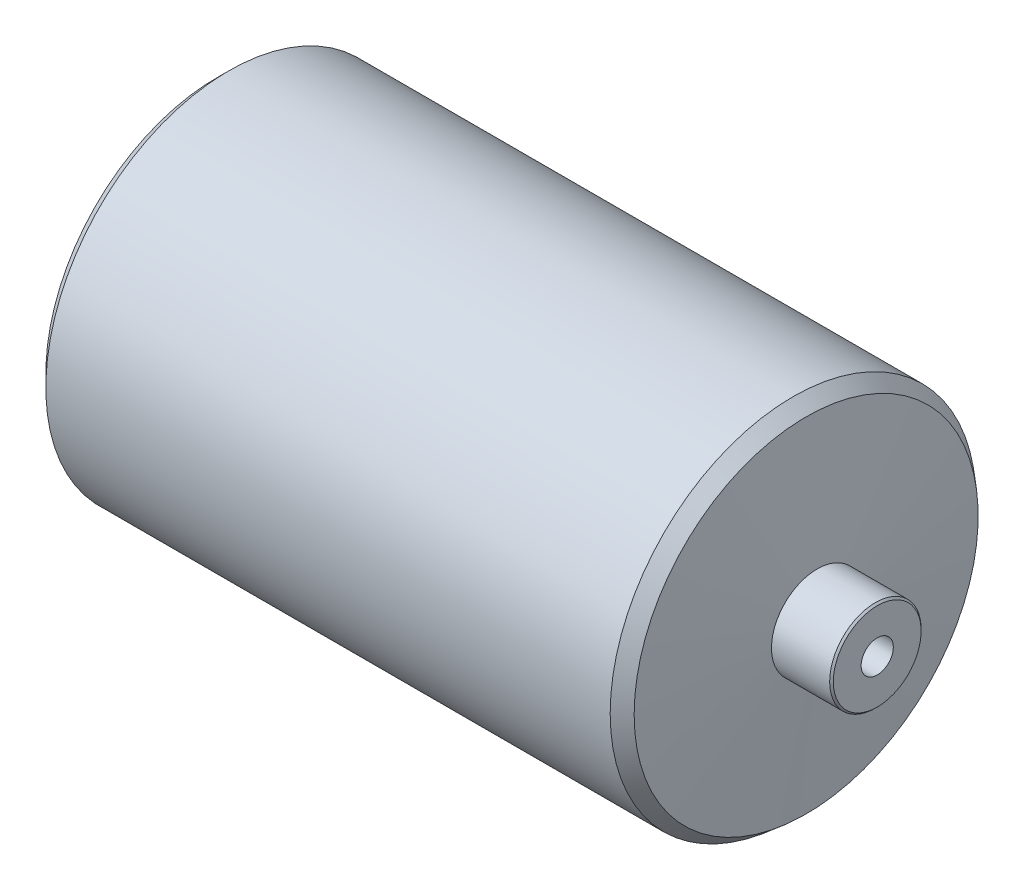
SolidWorks part; units mm, degrees
ref_plane "前基準面" through (0, 0, 0) normal (0, 0, 1) x (1, 0, 0)
ref_plane "上基準面" through (0, 0, 0) normal (0, 1, 0) x (1, 0, 0)
ref_plane "右基準面" through (0, 0, 0) normal (1, 0, 0) x (0, 0, -1)
sketch "草圖1" plane through (0, 0, 0) normal (0, 0, 1) x (1, 0, 0)
  line L1 (0, 0) -> (16.5, 0)
  line L2 (0, 0) -> (0, 12.5)
  line L3 (0, 12.5) -> (16.5, 12.5)
  line L4 (16.5, 0) -> (16.5, 12.5)
  line L5 (16.5, 0) -> (183.6, 0)
  line L6 (16.5, 0) -> (16.5, 50)
  line L7 (16.5, 50) -> (183.6, 50)
  line L8 (183.6, 0) -> (183.6, 50)
  line L9 (183.6, 0) -> (200, 0)
  line L10 (183.6, 0) -> (183.6, 12.5)
  line L11 (183.6, 12.5) -> (200, 12.5)
  line L12 (200, 0) -> (200, 12.5)
  dimension "D1" = 200
  dimension "D2" = 16.4
  dimension "D3" = 16.5
  dimension "D4" = 12.5
  dimension "D5" = 12.5
  dimension "D6" = 50
revolve "旋轉1" add sketch "草圖1" angle 360 about L5
sketch "草圖2" plane through (0, 0, 0) normal (0, 0, 1) x (1, 0, 0)
  line L0 (0, 12.5) -> (16.5, 12.5)
  line L1 (16.5, 12.5) -> (20.558, 58.8837)
  line L2 (200, 12.5) -> (183.6, 12.5)
  line L3 (183.6, -50) -> (183.6, 50) construction
  line L4 (183.6, -12.5) -> (183.6, 12.5) construction
  line L5 (183.6, 12.5) -> (178.9819, 65.2855)
  line L6 (20.558, 58.8837) -> (178.9819, 65.2855)
  line L7 (200, 12.5) -> (186.8731, 74.8434)
  line L8 (186.8731, 74.8434) -> (1.0252, 63.1739)
  line L9 (1.0252, 63.1739) -> (0, 12.5)
  line L10 (0, 0) -> (-38.6891, 0)
  dimension "D1" = 95
  dimension "D2" = 95
revolve "除料-旋轉1" cut sketch "草圖2" angle 360 about L10
chamfer "導角1" distance 0.5 angle 45 2 edges at (200, 0, 12.5) (0, 0, 12.5)
chamfer "導角2" distance 3 angle 45 2 edges at (180.3192, 0, 50) (19.7808, 0, -50)
hole_wizard "M10x1.25 螺紋孔1" positions "3D草圖1" profile "草圖5" tap size "M10x1.25" standard "ISO"
sketch3d "3D草圖1"
  circle A0 centre (200, 0, 0) radius 12 construction
  circle A1 centre (200, 0, 0) radius 12
  point P0 (200, 0, 0)
  point P3 (0, 0, 0)
  point P6 (212, 0, 0)
  point P8 (212, 0, 0)
  point P9 (200, 0, 0)
sketch "草圖5" plane through (200, 0, 0) normal (0, 1, 0) x (0, 0, -1)
  line L0 (0, 0) -> (0, 61.6438)
  line L1 (0, 61.6438) -> (4.4, 59)
  line L2 (4.4, 59) -> (4.4, 0)
  line L5 (4.4, 0) -> (0, 0)
  line L10 (0, 61.6438) -> (-4.4, 59) construction
  line L11 (0, -6.35) -> (0, 107.95) construction
  dimension "螺孔鑽直徑" = 8.8
  dimension "螺孔鑽深度" = 59
  dimension "導頭角度" = 118
cosmetic thread "鑽孔螺紋1" parameters "D1"=50, "D2"=10
hole_wizard "M10x1.25 螺紋孔2" positions "草圖6" profile "草圖7" tap size "M10x1.25" standard "ISO"
sketch "草圖6" plane through (0, 0, 0) normal (-1, 0, 0) x (0, 0, 1)
  point P0 (0, 0)
sketch "草圖7" plane through (0, 0, 0) normal (0, 1, 0) x (0, 0, 1)
  line L0 (0, 0) -> (0, 61.6438)
  line L1 (0, 61.6438) -> (4.4, 59)
  line L2 (4.4, 59) -> (4.4, 0)
  line L5 (4.4, 0) -> (0, 0)
  line L10 (0, 61.6438) -> (-4.4, 59) construction
  line L11 (0, -6.35) -> (0, 107.95) construction
  dimension "螺孔鑽直徑" = 8.8
  dimension "螺孔鑽深度" = 59
  dimension "導頭角度" = 118
cosmetic thread "鑽孔螺紋2" parameters "D1"=50, "D2"=10
